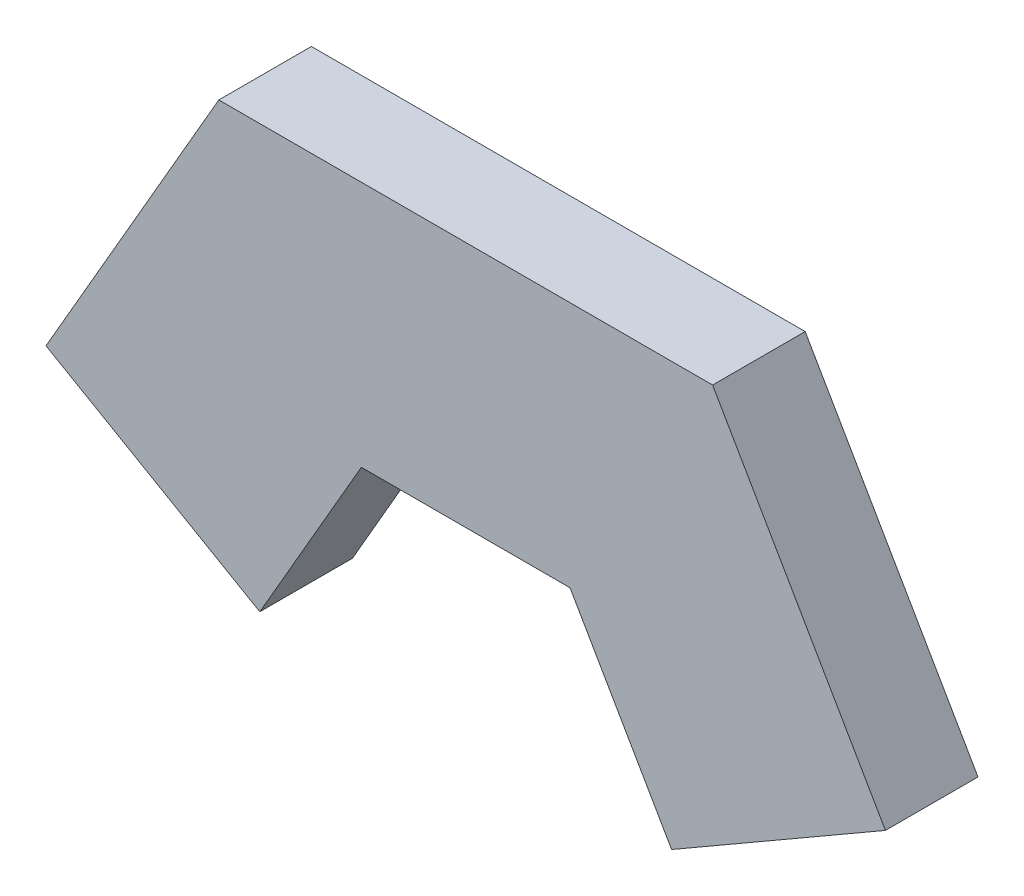
SolidWorks part; units mm, degrees
material "Balsa"
ref_plane "Front Plane" through (0, 0, 0) normal (0, 0, 1) x (1, 0, 0)
ref_plane "Top Plane" through (0, 0, 0) normal (0, 1, 0) x (1, 0, 0)
ref_plane "Right Plane" through (0, 0, 0) normal (1, 0, 0) x (0, 0, -1)
sketch "Sketch1" plane through (0, 0, 0) normal (0, 0, 1) x (1, 0, 0)
  line L0 (-21.59, -15.3979) -> (-12.7, 0)
  line L1 (-12.7, 0) -> (12.7, 0)
  line L2 (12.7, 0) -> (21.59, -15.3979)
  line L3 (21.59, -15.3979) -> (10.5915, -21.7479)
  line L4 (10.5915, -21.7479) -> (5.3677, -12.7)
  line L5 (5.3677, -12.7) -> (-5.3677, -12.7)
  line L6 (-5.3677, -12.7) -> (-10.5915, -21.7479)
  line L7 (-10.5915, -21.7479) -> (-21.59, -15.3979)
  line L8 (0, -55) -> (0, 55) construction
  line L9 (12.7, 0) -> (6.35, 0)
  line L15 (-12.7, 0) -> (-6.35, 0)
  point P8 (0, 0)
  dimension "D1" = 120
  dimension "D2" = 25.4
  dimension "D3" = 12.7
  dimension "D4" = 10.4477
  dimension "D5" = 17.78
extrude "Boss-Extrude1" add sketch "Sketch1" along normal blind 4.7625
